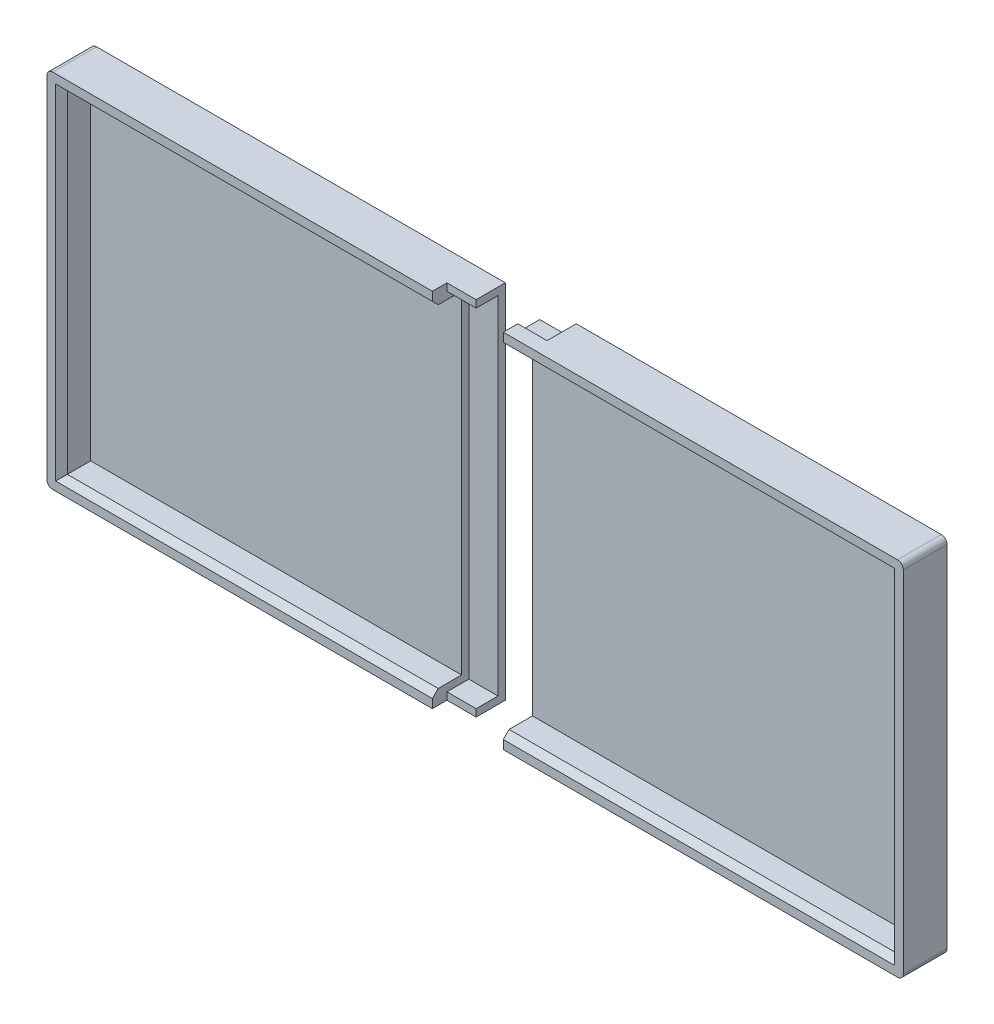
SolidWorks part; units mm, degrees
ref_plane "Front Plane" through (0, 0, 0) normal (0, 0, 1) x (1, 0, 0)
ref_plane "Top Plane" through (0, 0, 0) normal (0, 1, 0) x (1, 0, 0)
ref_plane "Right Plane" through (0, 0, 0) normal (1, 0, 0) x (0, 0, -1)
sketch "Sketch1" plane through (0, 0, 0) normal (0, 0, 1) x (1, 0, 0)
  line L1 (-80.645, 72.263) -> (80.645, 72.263)
  line L2 (-80.645, 72.263) -> (-80.645, -72.263)
  line L3 (-80.645, -72.263) -> (80.645, -72.263)
  line L5 (80.645, -78.613) -> (-86.995, -78.613)
  line L7 (80.645, 78.613) -> (-86.995, 78.613)
  line L8 (-86.995, -78.613) -> (-86.995, 78.613)
  line L13 (80.645, 72.263) -> (80.645, 78.613)
  line L14 (80.645, -72.263) -> (80.645, -78.613)
  point P4 (0, 72.263)
  point P6 (-80.645, 0)
  point P7 (0, 0)
  dimension "D1" = 6.35
  dimension "D2" = 6.35
  dimension "D3" = 161.29
  dimension "D4" = 144.526
  dimension "D5" = 6.35
extrude "Boss-Extrude1" add sketch "Sketch1" along normal blind 12.7
sketch "Sketch2" plane through (0, 0, 0) normal (0, 0, -1) x (-1, 0, 0)
  line L10 (86.995, 78.613) -> (-80.645, 78.613)
  line L12 (86.995, 78.613) -> (86.995, -78.613)
  line L13 (86.995, -78.613) -> (-80.645, -78.613)
  line L15 (-80.645, 78.613) -> (-80.645, -78.613)
  point P6 (0, 0)
extrude "Boss-Extrude2" add sketch "Sketch2" along normal blind 6.35
fillet "Fillet1" radius 2.54 2 edges at (-86.995, -78.613, 3.175) (-86.995, 78.613, 3.175)
fillet "Fillet2" radius 2.54 3 edges at (-80.645, 0, 12.7) (0, 72.263, 12.7) (0, -72.263, 12.7) profile chamfer
ref_plane "Plane2" through (0, 0, 0) normal (0, 1, 0) x (1, 0, 0)
sketch "Sketch7" plane through (0, 0, 0) normal (0, 0, 1) x (1, 0, 0)
  line L0 (80.645, 78.613) -> (-84.455, 78.613) construction
  line L1 (111.4821, 78.613) -> (285.4721, 78.613)
  line L2 (111.4821, 78.613) -> (111.4821, -78.613)
  line L3 (111.4821, -78.613) -> (285.4721, -78.613)
  line L4 (285.4721, 78.613) -> (285.4721, -78.613)
  line L5 (-84.455, -78.613) -> (80.645, -78.613) construction
  line L7 (111.4821, 72.263) -> (279.1221, 72.263)
  line L8 (111.4821, 72.263) -> (111.4821, -72.263)
  line L9 (111.4821, -72.263) -> (279.1221, -72.263)
  line L10 (279.1221, 72.263) -> (279.1221, -72.263)
  dimension "D1" = 173.99
  dimension "D2" = 6.35
  dimension "D3" = 6.35
  dimension "D4" = 6.35
extrude "Boss-Extrude6" add sketch "Sketch7" along normal blind 12.7 separate body contours L7 L10 L9 L2 L3 L4 L1
sketch "Sketch8" plane through (0, 0, 0) normal (0, 0, -1) x (-1, 0, 0)
  line L1 (-285.4721, 78.613) -> (-111.4821, 78.613)
  line L2 (-285.4721, 78.613) -> (-285.4721, -78.613)
  line L3 (-285.4721, -78.613) -> (-111.4821, -78.613)
  line L4 (-111.4821, 78.613) -> (-111.4821, -78.613)
extrude "Boss-Extrude7" add sketch "Sketch8" along normal blind 6.35
chamfer "Chamfer1" distance 2.54 angle 45 3 edges at (195.3021, -72.263, 12.7) (279.1221, 0, 12.7) (195.3021, 72.263, 12.7)
fillet "Fillet4" radius 2.54 2 edges at (285.4721, -78.613, 3.175) (285.4721, 78.613, 3.175)
sketch "Sketch9" plane through (80.645, 0, 0) normal (1, 0, 0) x (0, 0, -1)
  line L0 (6.35, -78.613) -> (-6.3559, -78.613)
  line L1 (-12.7, -78.613) -> (6.35, -78.613) construction
  line L2 (-6.3559, -78.613) -> (-6.3559, -75.438)
  line L3 (-6.3559, -75.438) -> (3.175, -75.438)
  line L4 (3.175, -75.438) -> (3.175, 75.438)
  line L5 (-6.3559, 75.438) -> (-6.3559, 78.613)
  line L6 (-12.7, 78.613) -> (6.35, 78.613) construction
  line L7 (-6.3559, 78.613) -> (6.35, 78.613)
  line L8 (6.35, 78.613) -> (6.35, -78.613)
  line L9 (-6.3559, 75.438) -> (3.175, 75.438)
  dimension "D1" = 3.175
  dimension "D2" = 3.175
  dimension "D3" = 3.175
extrude "Boss-Extrude8" add sketch "Sketch9" along normal blind 12.7
sketch "Sketch10" plane through (111.4821, 0, 0) normal (-1, 0, 0) x (0, 0, 1)
  line L0 (-6.35, 78.613) -> (6.3559, 78.613)
  line L1 (6.3559, 78.613) -> (6.3559, 75.438)
  line L2 (6.3559, 75.438) -> (-3.175, 75.438)
  line L3 (-3.175, 75.438) -> (-3.175, -75.438)
  line L4 (6.3559, -75.438) -> (6.3559, -78.613)
  line L5 (6.3559, -78.613) -> (-6.35, -78.613)
  line L6 (-6.35, -78.613) -> (-6.35, 78.613)
  line L7 (6.3559, -75.438) -> (-3.175, -75.438)
  line L8 (12.7, -78.613) -> (-6.35, -78.613) construction
  line L9 (12.7, 78.613) -> (-6.35, 78.613) construction
  point P8 (0, 0)
  dimension "D1" = 3.175
  dimension "D2" = 3.175
  dimension "D3" = 3.175
extrude "Cut-Extrude1" cut sketch "Sketch10" against normal blind 12.7
